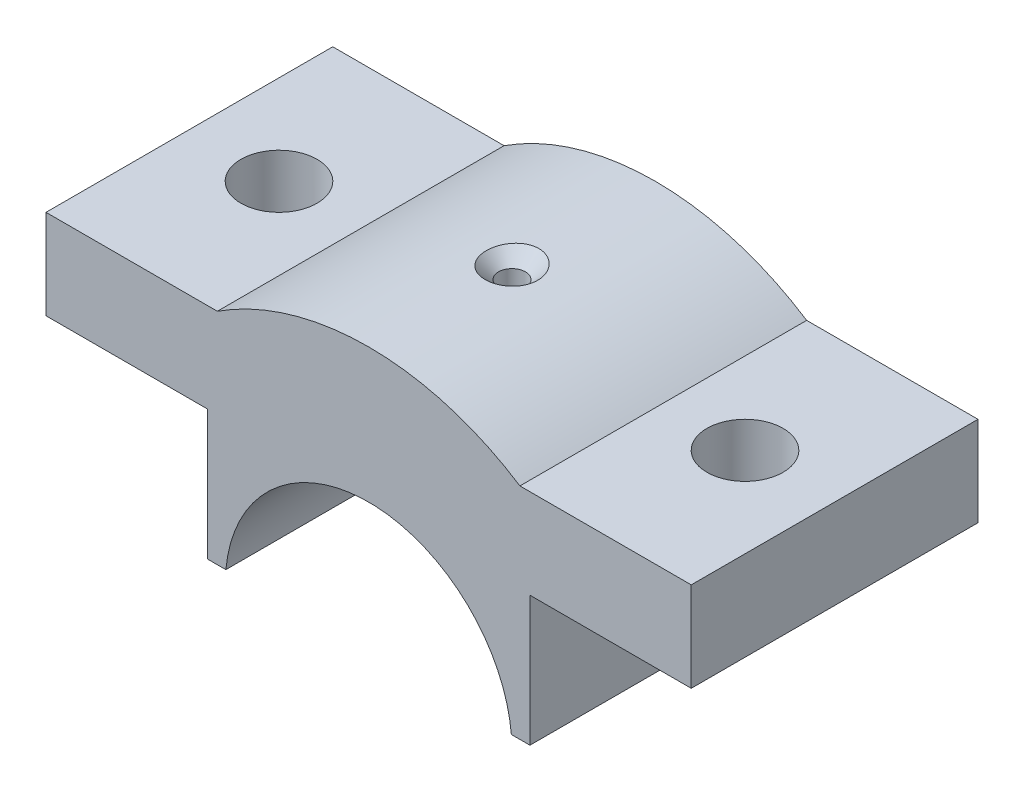
SolidWorks part; units mm, degrees
ref_plane "Front Plane" through (0, 0, 0) normal (0, 0, 1) x (1, 0, 0)
ref_plane "Top Plane" through (0, 0, 0) normal (0, 1, 0) x (1, 0, 0)
ref_plane "Right Plane" through (0, 0, 0) normal (1, 0, 0) x (0, 0, -1)
sketch "Sketch1" plane through (0, 0, 0) normal (0, 0, 1) x (1, 0, 0)
  line L0 (0, -34100) -> (0, 34100) construction
  line L1 (-33.7639, 52) -> (-72.0039, 52)
  line L2 (-72.0039, 52) -> (-72.0039, 32)
  line L3 (-72.0039, 32) -> (-36.0039, 32)
  line L4 (-36.0039, 32) -> (-36.0039, 3)
  line L5 (-36.0039, 3) -> (-31.8639, 3)
  line L7 (36.0039, 3) -> (31.8639, 3)
  line L8 (36.0039, 32) -> (36.0039, 3)
  line L9 (72.0039, 32) -> (36.0039, 32)
  line L10 (72.0039, 52) -> (72.0039, 32)
  line L11 (33.7639, 52) -> (72.0039, 52)
  arc A1 (31.8639, 3) -> (-31.8639, 3) centre (0, 0) ccw
  arc A2 (33.7639, 52) -> (-33.7639, 52) centre (0, 0) ccw
extrude "Boss-Extrude1" add sketch "Sketch1" along normal blind 64
sketch "Sketch2" plane through (0, 52, 0) normal (0, 1, 0) x (1, 0, 0)
  line L0 (-33.7639, -64) -> (-72.0039, -64) construction
  line L1 (-72.0039, -64) -> (-72.0039, 0) construction
  circle A0 centre (-52.0039, -32) radius 8.5
  dimension "D1" = 32
  dimension "D3" = 17
  dimension "D2" = 20
extrude "Cut-Extrude1" cut sketch "Sketch2" against normal through all
mirror "Mirror1" about plane through (0, 0, 0) normal (1, 0, 0) of "Cut-Extrude1"
ref_plane "Plane1" through (0, 62, 0) normal (0, 1, 0) x (1, 0, 0)
sketch "Sketch3" plane through (0, 62, 0) normal (0, 1, 0) x (1, 0, 0)
  circle A0 centre (0, -32) radius 3
extrude "Cut-Extrude2" cut sketch "Sketch3" against normal through all
sketch "Sketch4" plane through (0, 62, 0) normal (0, 1, 0) x (1, 0, 0)
  circle A0 centre (0, -32) radius 6
extrude "Cut-Extrude3" cut sketch "Sketch4" against normal blind 3 draft 45
